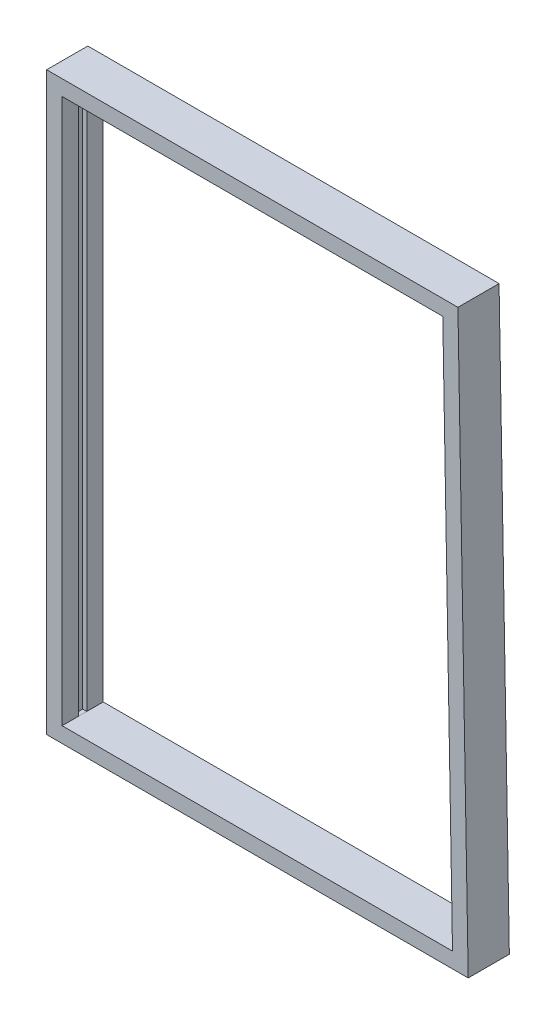
SolidWorks part; units mm, degrees
ref_plane "Front Plane" through (0, 0, 0) normal (0, 0, 1) x (1, 0, 0)
ref_plane "Top Plane" through (0, 0, 0) normal (0, 1, 0) x (1, 0, 0)
ref_plane "Right Plane" through (0, 0, 0) normal (1, 0, 0) x (0, 0, -1)
sketch "Sketch2" plane through (0, 0, 0) normal (0, 0, 1) x (1, 0, 0)
  line L0 (-520.7, 711.2) -> (495.3, 710.9732)
  line L5 (495.3, 710.9732) -> (520.7, -711.2)
  line L6 (-520.7, -711.2) -> (520.7, -711.2)
  line L7 (-520.7, 711.2) -> (-520.7, -711.2)
  line L8 (-482.6, 673.0915) -> (457.8742, 672.8815)
  line L9 (457.8742, 672.8815) -> (481.9135, -673.1)
  line L10 (-482.6, -673.1) -> (481.9135, -673.1)
  line L11 (-482.6, 673.0915) -> (-482.6, -673.1)
  dimension "D1" = 1422.4
  dimension "D2" = 1016
  dimension "D3" = 38.1
extrude "Boss-Extrude1" add sketch "Sketch2" along normal blind 101.6
sketch "Sketch3" plane through (469.742, 8.3896, 0) normal (-0.9998, -0.0179, 0) x (0, 0, 1)
  line L3 (40.64, 664.5998) -> (60.96, 664.5998)
  line L12 (40.64, 664.5998) -> (40.64, -681.6002)
  line L13 (40.64, -681.6002) -> (60.96, -681.6002)
  line L14 (60.96, 664.5998) -> (60.96, -681.6002)
  point P2 (50.8, -8.5002)
  dimension "D2" = 20.32
extrude "Cut-Extrude1" cut sketch "Sketch3" against normal blind 10.16
sketch "Sketch4" plane through (-482.6, 0, 0) normal (1, 0, 0) x (0, 0, -1)
  line L3 (-60.96, 673.0957) -> (-40.64, 673.0957)
  line L12 (-60.96, 673.0957) -> (-60.96, -673.1043)
  line L13 (-60.96, -673.1043) -> (-40.64, -673.1043)
  line L14 (-40.64, 673.0957) -> (-40.64, -673.1043)
  point P2 (-50.8, -0.0043)
  dimension "D2" = 1346.2
  dimension "D3" = 20.32
extrude "Cut-Extrude2" cut sketch "Sketch4" against normal blind 10.16
